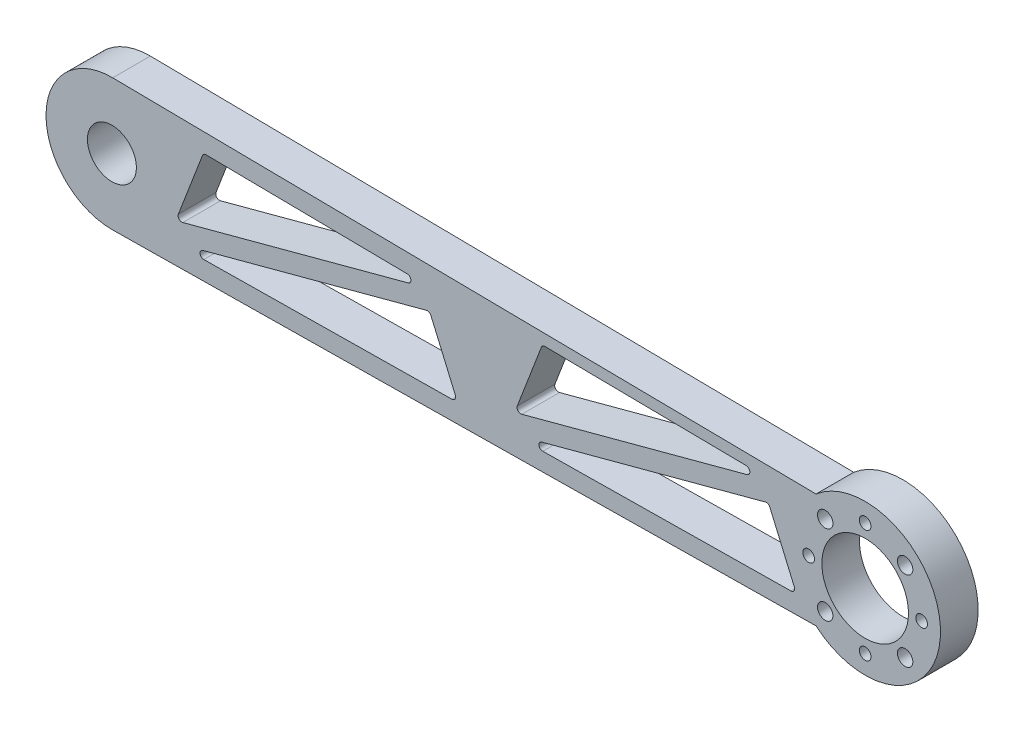
SolidWorks part; units mm, degrees
ref_plane "前视基准面" through (0, 0, 0) normal (0, 0, 1) x (1, 0, 0)
ref_plane "上视基准面" through (0, 0, 0) normal (0, 1, 0) x (1, 0, 0)
ref_plane "右视基准面" through (0, 0, 0) normal (1, 0, 0) x (0, 0, -1)
sketch "草图1" plane through (0, 0, 0) normal (0, 0, 1) x (1, 0, 0)
  line L0 (0.2188, 17.4986) -> (200.1875, 14.9988)
  line L1 (0, 0) -> (200, 0) construction
  line L2 (0.2188, -17.4986) -> (200.1875, -14.9988)
  circle A0 centre (0, 0) radius 17.5
  circle A1 centre (200, 0) radius 15
  dimension "D1" = 35
  dimension "20" = 30
  dimension "D3" = 200
extrude "凸台-拉伸1" add sketch "草图1" along normal blind 10
sketch "草图2" plane through (0, 0, 10) normal (0, 0, 1) x (1, 0, 0)
  circle A0 centre (0, 0) radius 6.5
  dimension "D1" = 13
extrude "切除-拉伸1" cut sketch "草图2" against normal blind 10
sketch "草图3" plane through (0, 0, 10) normal (0, 0, 1) x (1, 0, 0)
  line L0 (24.289, 12.1973) -> (85.6581, 11.4302)
  line L1 (85.6581, 11.4302) -> (16.9374, -6.9794)
  line L2 (16.9374, -6.9794) -> (24.289, 12.1973)
  line L3 (16.4146, -12.2958) -> (84.3461, 5.9024)
  line L4 (84.3461, 5.9024) -> (91.7811, -11.3536)
  line L5 (91.7811, -11.3536) -> (16.4146, -12.2958)
  line L6 (0.2188, -17.4986) -> (200.1875, -14.9988) construction
  line L7 (0.2188, 17.4986) -> (200.1875, 14.9988) construction
  line L8 (100.2031, 16.2487) -> (100.2031, -16.2487) construction
  line L9 (106.9328, -6.0644) -> (114.2844, 13.1124)
  line L10 (114.2844, 13.1124) -> (175.6535, 12.3452)
  line L11 (175.6535, 12.3452) -> (106.9328, -6.0644)
  line L12 (181.7765, -10.4386) -> (106.41, -11.3808)
  line L13 (106.41, -11.3808) -> (174.3414, 6.8174)
  line L14 (174.3414, 6.8174) -> (181.7765, -10.4386)
  dimension "D1" = 5
  dimension "D2" = 5
  dimension "D3" = 5
  dimension "D4" = 2
extrude "切除-拉伸2" cut sketch "草图3" against normal blind 10 contours L2 L0 L1 | L5 L3 L4 | L9 L10 L11 | L12 L13 L14
fillet "圆角1" radius 1 12 edges at (174.3414, 6.8174, 5) (181.7765, -10.4386, 5) (175.6535, 12.3452, 5) (106.41, -11.3808, 5) (106.9328, -6.0644, 5) (114.2844, 13.1124, 5) (84.3461, 5.9024, 5) (91.7811, -11.3536, 5) (16.4146, -12.2958, 5) (24.289, 12.1973, 5) (85.6581, 11.4302, 5) (16.9374, -6.9794, 5)
sketch "草图4" plane through (0, 0, 10) normal (0, 0, 1) x (1, 0, 0)
  line L0 (0.2188, 17.4986) -> (200.1875, 14.9988) construction
  line L1 (186.9598, 15.1642) -> (200.1875, 14.9988)
  line L2 (0.2188, -17.4986) -> (200.1875, -14.9988) construction
  line L3 (186.9598, -15.1642) -> (200.1875, -14.9988)
  arc A0 (186.9598, -15.1642) -> (186.9598, 15.1642) centre (200, 0) ccw
  arc A1 (200.1875, -14.9988) -> (200.1875, 14.9988) centre (200, 0) ccw construction
  arc A2 (200.1875, -14.9988) -> (200.1875, 14.9988) centre (200, 0) ccw
  dimension "D1" = 40
extrude "凸台-拉伸2" add sketch "草图4" against normal up to surface (10 mm away) contours L1 A0 L3 A2 up to face at (130.4815, 6.4286, 0)
sketch "草图5" plane through (0, 0, 10) normal (0, 0, 1) x (1, 0, 0)
  line L0 (189.3934, 10.6066) -> (200, 0)
  line L1 (200, 0) -> (200, 15) construction
  circle A0 centre (200, 0) radius 15 construction
  circle A1 centre (200, 15) radius 1.55
  circle A2 centre (215, 0) radius 1.55
  circle A3 centre (200, -15) radius 1.55
  circle A4 centre (185, 0) radius 1.55
  circle A5 centre (189.3934, 10.6066) radius 2.05
  circle A6 centre (210.6066, 10.6066) radius 2.05
  circle A7 centre (210.6066, -10.6066) radius 2.05
  circle A8 centre (189.3934, -10.6066) radius 2.05
  point P14 (200, 0)
  point P23 (200, 0)
  dimension "D1" = 30
  dimension "D2" = 3.1
  dimension "D5" = 4.1
  dimension "D4" = 45
  dimension "D3" = 4
  dimension "D6" = 4
extrude "切除-拉伸3" cut sketch "草图5" against normal blind 10
sketch "草图6" plane through (0, 0, 10) normal (0, 0, 1) x (1, 0, 0)
  circle A0 centre (200, 0) radius 11.5
  dimension "D1" = 23
extrude "切除-拉伸4" cut sketch "草图6" against normal blind 10
